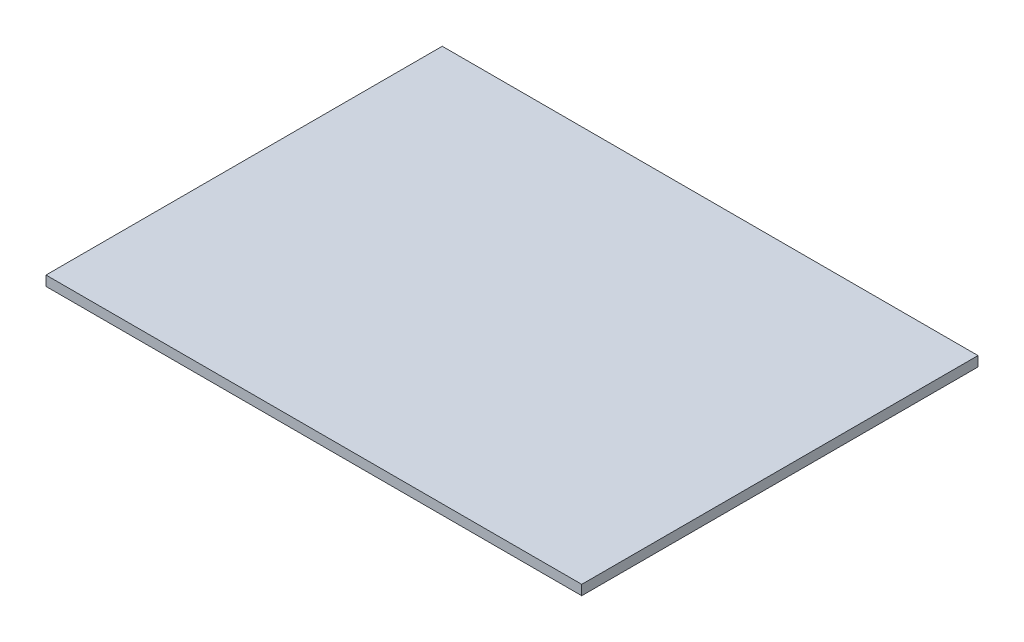
SolidWorks part; units mm, degrees
ref_plane "Alzado" through (0, 0, 0) normal (0, 0, 1) x (1, 0, 0)
ref_plane "Planta" through (0, 0, 0) normal (0, 1, 0) x (1, 0, 0)
ref_plane "Vista lateral" through (0, 0, 0) normal (1, 0, 0) x (0, 0, -1)
sketch "Croquis1" plane through (0, 0, 0) normal (0, 1, 0) x (1, 0, 0)
  line L0 (0, 300) -> (0, -300) construction
  line L1 (-405.6, -300) -> (405.6, -300)
  line L2 (-405.6, -300) -> (-405.6, 300)
  line L3 (-405.6, 300) -> (405.6, 300)
  line L4 (405.6, -300) -> (405.6, 300)
  line L5 (-405.6, -300) -> (405.6, 300) construction
  line L6 (-405.6, 300) -> (405.6, -300) construction
  line L7 (-405.6, 0) -> (405.6, 0) construction
  point P0 (0, 0)
  point P10 (0, 0)
  dimension "D1" = 811.2
  dimension "D2" = 600
extrude "Saliente-Extruir1" add sketch "Croquis1" along normal blind 15
sketch "Croquis2" plane through (0, 15, 0) normal (0, 1, 0) x (1, 0, 0)
  line L0 (0, 300) -> (0, -300) construction
  line L1 (405.6, 300) -> (-405.6, 300) construction
  line L2 (-405.6, -300) -> (405.6, -300) construction
  line L3 (-405.6, 0) -> (405.6, 0) construction
  line L4 (-405.6, 300) -> (-405.6, -300) construction
  line L5 (405.6, -300) -> (405.6, 300) construction
  line L6 (-187.5, 300) -> (-187.5, -300) construction
  line L7 (187.5, 300) -> (187.5, -300) construction
  line L8 (-405.6, 187.5) -> (405.6, 187.5) construction
  line L9 (-405.6, -187.5) -> (405.6, -187.5) construction
  dimension "D1" = 187.5
  dimension "D2" = 187.5
  dimension "D3" = 187.5
  dimension "D4" = 187.5
